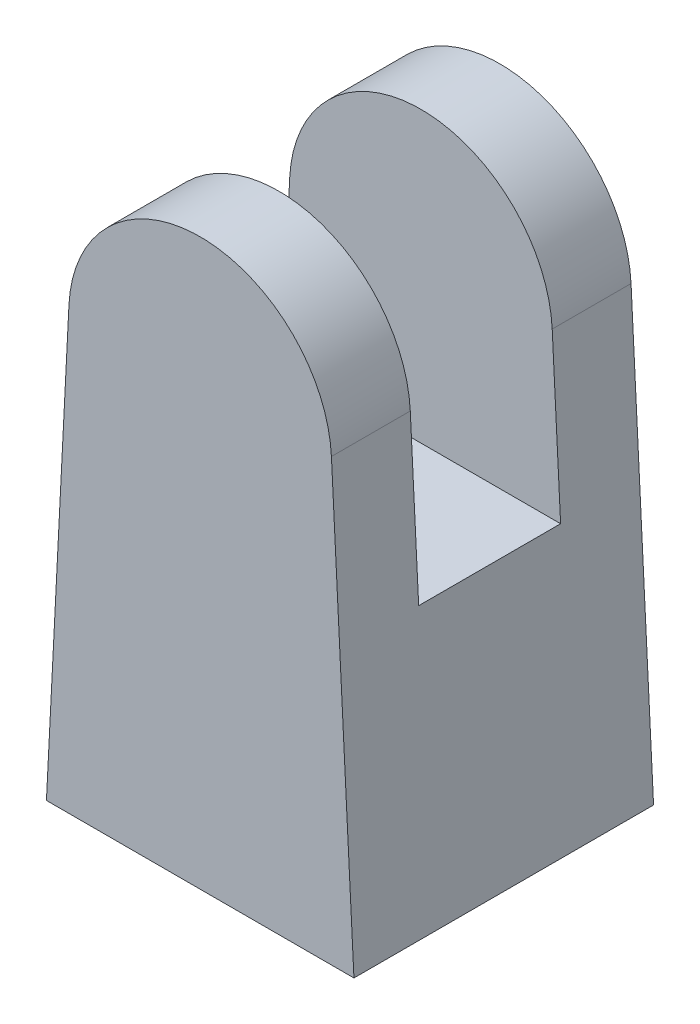
SolidWorks part; units mm, degrees
ref_plane "Front Plane" through (0, 0, 0) normal (0, 0, 1) x (1, 0, 0)
ref_plane "Top Plane" through (0, 0, 0) normal (0, 1, 0) x (1, 0, 0)
ref_plane "Right Plane" through (0, 0, 0) normal (1, 0, 0) x (0, 0, -1)
sketch "Sketch1" plane through (0, 0, 0) normal (0, 0, 1) x (1, 0, 0)
  line L0 (0, 0) -> (-165, 0) construction
  line L1 (-165, -58.5) -> (-165, 58.5)
  line L2 (-165, 58.5) -> (2.5526, 49.9348)
  line L3 (-165, -58.5) -> (2.5526, -49.9348)
  arc A0 (2.5526, -49.9348) -> (2.5526, 49.9348) centre (0, 0) ccw
  dimension "D1" = 100
  dimension "D2" = 165
  dimension "D3" = 58.5
extrude "Boss-Extrude1" add sketch "Sketch1" along normal mid plane 114
sketch "Sketch2" plane through (-165, 0, 0) normal (-1, 0, 0) x (0, 0, 1)
  circle A0 centre (0, 0) radius 37.5
  dimension "D1" = 75
extrude "Boss-Extrude2" add sketch "Sketch2" along normal blind 2
sketch "Sketch3" plane through (0, 0, 0) normal (0, 1, 0) x (1, 0, 0)
  line L0 (50, -57) -> (50, 57) construction
  line L1 (53.9782, 27) -> (-60, 27)
  line L2 (53.9782, 27) -> (53.9782, -27)
  line L3 (53.9782, -27) -> (-60, -27)
  line L4 (-60, 27) -> (-60, -27)
  dimension "D1" = 54
  dimension "D2" = 110
  dimension "D3" = 27
extrude "Cut-Extrude1" cut sketch "Sketch3" against normal through all both and the other way through all
move or copy body "Body-Move/Copy1" bodies to move or copy 103 copy no rotation origin (0, 0, 0) rotation axis (0, 0, 1) rotation angle 90
